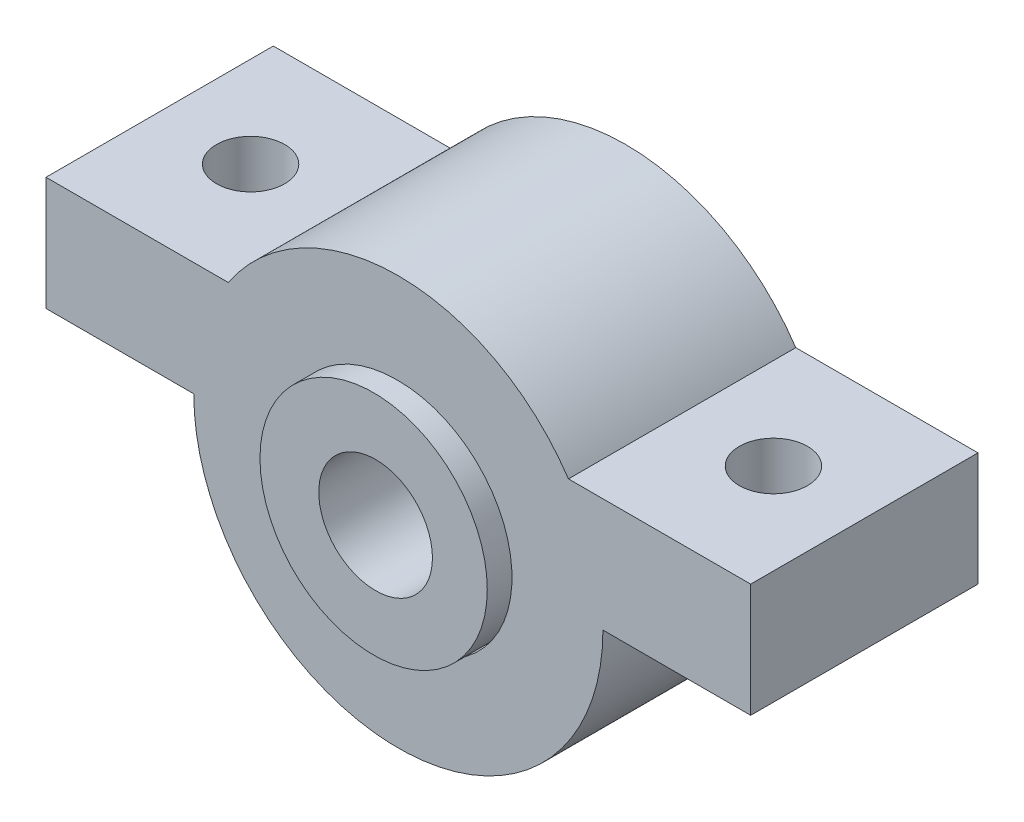
SolidWorks part; units mm, degrees
ref_plane "Front Plane" through (0, 0, 0) normal (0, 0, 1) x (1, 0, 0)
ref_plane "Top Plane" through (0, 0, 0) normal (0, 1, 0) x (1, 0, 0)
ref_plane "Right Plane" through (0, 0, 0) normal (1, 0, 0) x (0, 0, -1)
sketch "Sketch1" plane through (0, 0, 0) normal (0, 0, 1) x (1, 0, 0)
  line L1 (1.55, 0) -> (0.55, 0)
  line L2 (1.55, 0) -> (1.55, 0.5)
  line L3 (1.55, 0.5) -> (0.55, 0.5)
  line L4 (0.55, 0) -> (0.55, 0.5)
  line L5 (-1.55, 0) -> (-0.55, 0)
  line L6 (-1.55, 0) -> (-1.55, 0.5)
  line L7 (-1.55, 0.5) -> (-0.55, 0.5)
  line L8 (-0.55, 0) -> (-0.55, 0.5)
  circle A0 centre (0, 0) radius 0.25
  circle A1 centre (0, 0) radius 0.5
  circle A2 centre (0, 0) radius 0.9
  dimension "D1" = 0.5
  dimension "D2" = 0.55
  dimension "D3" = 1
  dimension "D5" = 1.8
  dimension "D4" = 0.55
  dimension "D6" = 0.5
  dimension "D7" = 0.5
  dimension "D8" = 1
  dimension "D9" = 1
extrude "Boss-Extrude1" add sketch "Sketch1" along normal blind 1 contours L3 A2 L7 L8 L5 L1 L4 A1 | A2 L1 L2 L3 | A2 L7 L6 L5
sketch "Sketch2" plane through (0, 0, 1) normal (0, 0, 1) x (1, 0, 0)
  circle A0 centre (0, 0) radius 0.25
  circle A1 centre (-0.0088, 0) radius 0.5
  dimension "D1" = 1
  dimension "D2" = 0.5
extrude "Boss-Extrude2" add sketch "Sketch2" along normal blind 11 and the other way blind 1.2
sketch "Sketch3" plane through (0, 0, -0.2) normal (0, 0, -1) x (-1, 0, 0)
  circle A0 centre (0.0088, 0) radius 0.6609
  dimension "D1" = 1.3218
extrude "Cut-Extrude3" cut sketch "Sketch3" against normal blind 0.1
sketch "Sketch4" plane through (0, 0, 12) normal (0, 0, 1) x (1, 0, 0)
  circle A0 centre (0, 0) radius 0.55
  dimension "D1" = 1.1
extrude "Cut-Extrude4" cut sketch "Sketch4" against normal blind 10.9
sketch "Sketch5" plane through (0, 0.5, 0) normal (0, 1, 0) x (1, 0, 0)
  line L1 (1.55, -1) -> (1.55, 0) construction
  line L3 (-1.55, -1) -> (-1.55, 0) construction
  line L4 (-1.55, -1) -> (-0.7483, -1) construction
  line L5 (1.55, -1) -> (0.7483, -1) construction
  circle A0 centre (1.15, -0.5) radius 0.15
  circle A1 centre (-1.15, -0.5) radius 0.15
  dimension "D1" = 0.3
  dimension "D2" = 0.3
  dimension "D3" = 0.4
  dimension "D4" = 0.4
  dimension "D5" = 0.5
  dimension "D6" = 0.5
extrude "Cut-Extrude5" cut sketch "Sketch5" against normal blind 10.9
scale "Scale1" bodies to scale 109 scale about origin uniform scaling yes scale factor 10
